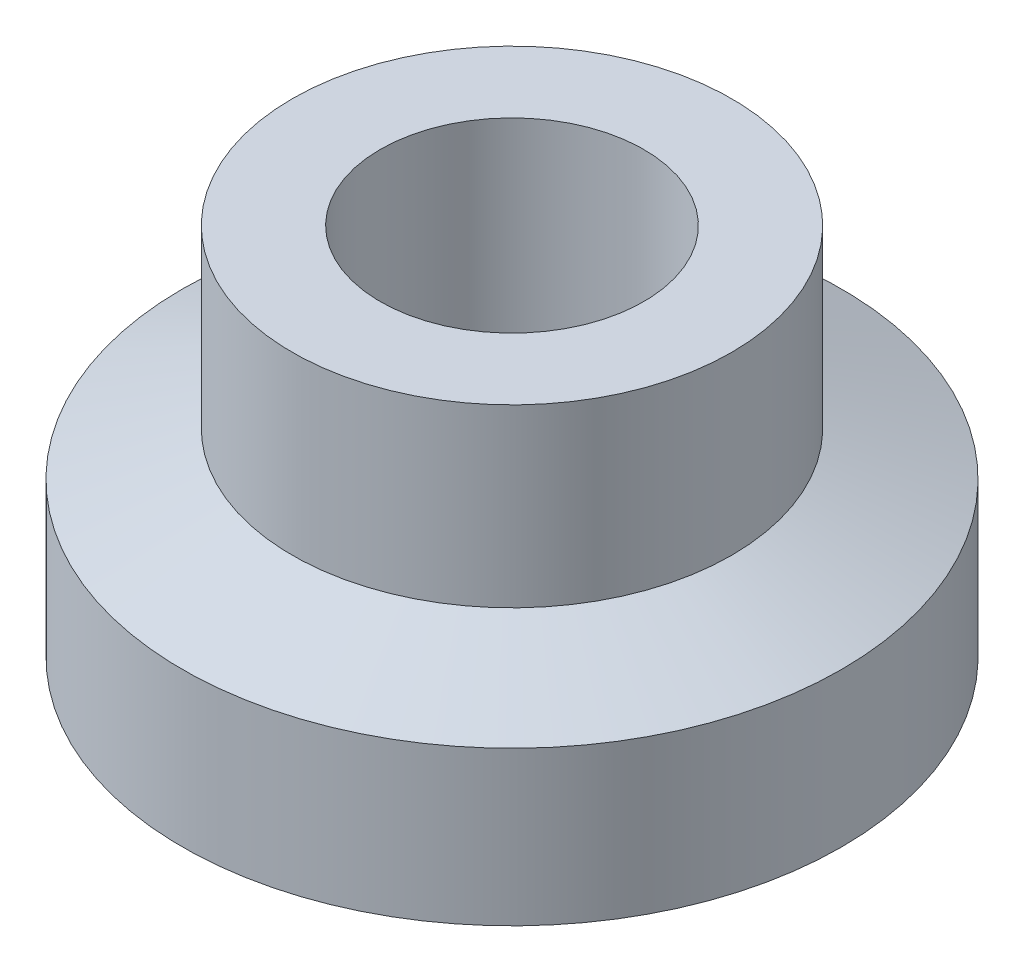
SolidWorks part; units mm, degrees
ref_plane "Front Plane" through (0, 0, 0) normal (0, 0, 1) x (1, 0, 0)
ref_plane "Top Plane" through (0, 0, 0) normal (0, 1, 0) x (1, 0, 0)
ref_plane "Right Plane" through (0, 0, 0) normal (1, 0, 0) x (0, 0, -1)
sketch "Sketch1" plane through (0, 0, 0) normal (0, 0, 1) x (1, 0, 0)
  line L0 (0, 0) -> (15, 0)
  line L1 (15, 0) -> (15, 7)
  line L2 (15, 7) -> (10, 9)
  line L3 (10, 9) -> (10, 17)
  line L4 (10, 17) -> (6, 17)
  line L5 (6, 17) -> (6, 5)
  line L6 (6, 5) -> (0, 5)
  line L7 (0, 5) -> (0, 0)
  dimension "D1" = 15
  dimension "D2" = 0
  dimension "D3" = 6
  dimension "D4" = 10
  dimension "D5" = 17
  dimension "D6" = 8
  dimension "D7" = 7
  dimension "D8" = 5
revolve "Revolve1" add sketch "Sketch1" angle 360 about L7
cosmetic thread "Cosmetic Thread1" parameters "D2"=14
hole_wizard "M4 Tapped Hole1" positions "3DSketch1" profile "Sketch2" tap size "M4" standard "ISO"
sketch3d "3DSketch1"
  point P0 (0, 0, 0)
  point P3 (0, 0, 0)
  point P5 (0, 0, 0)
  point P8 (0, 0, 0)
  point P10 (0, 0, 0)
  point P12 (0, 0, 0)
sketch "Sketch2" plane through (0, 0, 0) normal (1, 0, 0) x (0, 0, -1)
  line L0 (0, 0) -> (0, 11.5)
  line L1 (0, 11.5) -> (1.65, 10.5086)
  line L2 (1.65, 10.5086) -> (1.65, 0)
  line L5 (1.65, 0) -> (0, 0)
  line L10 (0, 11.5) -> (-1.65, 10.5086) construction
  line L11 (0, -6.35) -> (0, 107.95) construction
  dimension "Tap Drill Dia." = 3.3
  dimension "Tap Drill Depth" = 11.5
  dimension "Drill Angle" = 118
cosmetic thread "Hole Thread6" parameters "D1"=8, "D2"=4
